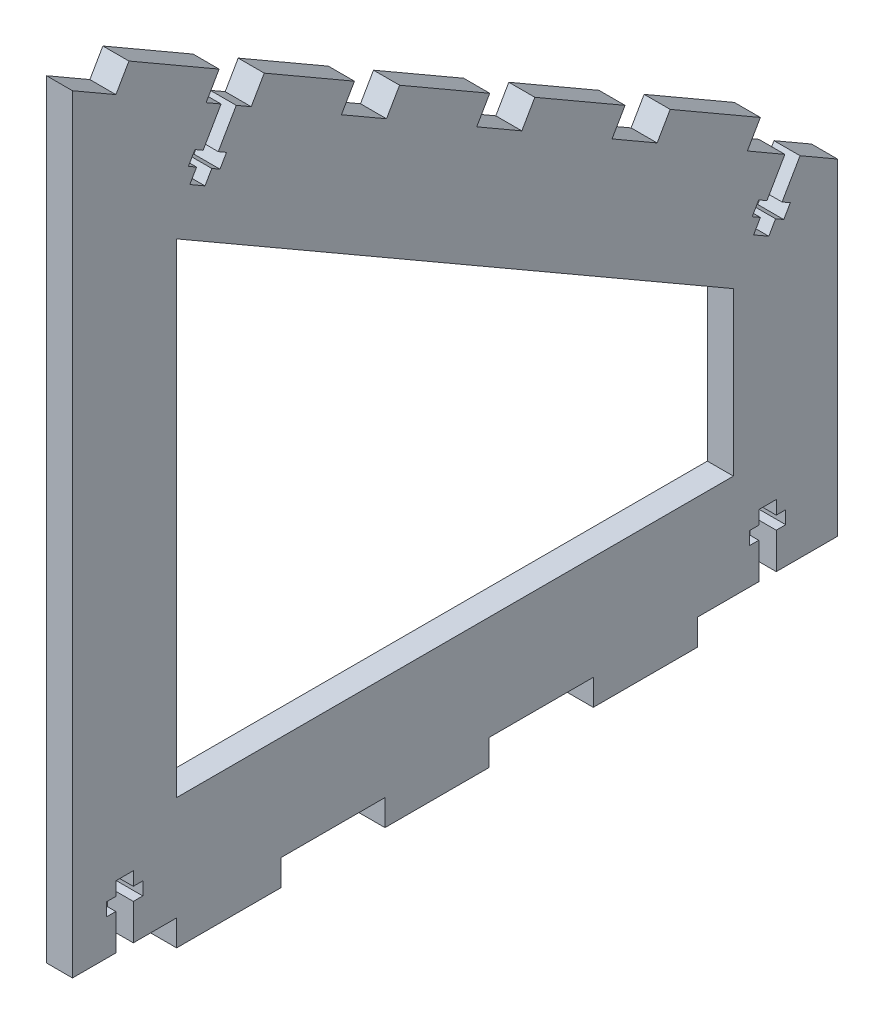
SolidWorks part; units mm, degrees
ref_plane "Front Plane" through (0, 0, 0) normal (0, 0, 1) x (1, 0, 0)
ref_plane "Top Plane" through (0, 0, 0) normal (0, 1, 0) x (1, 0, 0)
ref_plane "Right Plane" through (0, 0, 0) normal (1, 0, 0) x (0, 0, -1)
sketch "Sketch1" plane through (-32.0384, 0, 0) normal (-1, 0, 0) x (0, 0, 1)
  line L0 (-215.9, 95.25) -> (-215.9, 174.9125)
  line L1 (165.3114, 95.25) -> (152.9655, 95.25) construction
  line L2 (-215.9, 174.9125) -> (-29.3333, 282.6268)
  line L3 (-29.3333, 282.6268) -> (-29.3333, 95.25)
  line L4 (-29.3333, 95.25) -> (-215.9, 95.25)
  line L5 (-29.3333, 282.6268) -> (-40.1822, 276.3632) construction
  line L6 (-29.3333, 95.25) -> (-29.3333, 282.6268) construction
extrude "Boss-Extrude1" add sketch "Sketch1" along normal mid plane 6.35
sketch "Sketch2" plane through (-35.2134, 0, 0) normal (-1, 0, 0) x (0, 0, 1)
  line L4 (-190.5, 160.2478) -> (-190.5, 120.65)
  line L5 (-190.5, 160.2478) -> (-190.5, 120.65)
  line L14 (-54.7333, 120.65) -> (-54.7333, 238.6327)
  line L15 (-190.5, 120.65) -> (-54.7333, 120.65)
  line L16 (-54.7333, 238.6327) -> (-190.5, 160.2478)
  line L17 (-54.7333, 120.65) -> (-54.7333, 238.6327)
  line L18 (-190.5, 120.65) -> (-54.7333, 120.65)
  line L19 (-54.7333, 238.6327) -> (-190.5, 160.2478)
  dimension "D1" = 25.4
extrude "Cut-Extrude1" cut sketch "Sketch2" against normal blind 6.35
sketch "Sketch3" plane through (0, 224.6718, -129.7143) normal (0, 0.866, -0.5) x (1, 0, 0)
  line L0 (-35.2134, -115.91) -> (-35.2134, 99.5186) construction
  line L1 (-35.2134, 74.1186) -> (-28.8634, 74.1186)
  line L2 (-35.2134, 74.1186) -> (-35.2134, 48.7186)
  line L3 (-35.2134, 48.7186) -> (-28.8634, 48.7186)
  line L4 (-28.8634, 74.1186) -> (-28.8634, 48.7186)
  line L5 (-28.8634, -115.91) -> (-28.8634, 99.5186) construction
  dimension "D1" = 25.4
  dimension "D2" = 25.4
extrude "Boss-Extrude2" add sketch "Sketch3" along normal blind 6.35
pattern_linear "LPattern1" count 5 spacing 38.1 along (0, 0.5, 0.866) of "Boss-Extrude2"
sketch "Sketch4" plane through (0, 95.25, 0) normal (0, -1, 0) x (1, 0, 0)
  line L0 (-35.2134, -215.9) -> (-35.2134, -29.3333) construction
  line L1 (-35.2134, -54.7333) -> (-28.8634, -54.7333)
  line L2 (-35.2134, -54.7333) -> (-35.2134, -80.1333)
  line L3 (-35.2134, -80.1333) -> (-28.8634, -80.1333)
  line L4 (-28.8634, -54.7333) -> (-28.8634, -80.1333)
  line L5 (-28.8634, -215.9) -> (-28.8634, -29.3333) construction
  dimension "D1" = 25.4
  dimension "D2" = 25.4
extrude "Boss-Extrude3" add sketch "Sketch4" along normal blind 6.35
pattern_linear "LPattern2" count 3 spacing 50.8 along (0, 0, -1) of "Boss-Extrude3"
sketch "Sketch5" plane through (-28.8634, 0, 0) normal (1, 0, 0) x (0, 0, -1)
  line L0 (-152.9655, 95.25) -> (-165.3114, 95.25) construction
  line L1 (198.8167, 95.25) -> (198.8167, 119.6237) construction
  line L2 (215.9, 95.25) -> (181.7333, 95.25) construction
  line L3 (42.0333, 95.25) -> (42.0333, 127.2639) construction
  line L4 (54.7333, 95.25) -> (29.3333, 95.25) construction
  line L5 (-152.9655, 95.25) -> (-165.3114, 95.25) construction
  line B0 (196.6831, 95.25) -> (200.9503, 95.25)
  line B1 (200.9503, 107.188) -> (203.2617, 107.188)
  line B2 (203.2617, 107.188) -> (203.2617, 104.013)
  line B3 (203.2617, 104.013) -> (200.9503, 104.013)
  line B4 (200.9503, 104.013) -> (200.9503, 95.25)
  line B5 (200.9503, 107.188) -> (200.9503, 110.49)
  line B6 (200.9503, 110.49) -> (196.6831, 110.49)
  line B7 (196.6831, 107.188) -> (196.6831, 110.49)
  line B8 (196.6831, 104.013) -> (196.6831, 95.25)
  line B9 (194.3717, 104.013) -> (196.6831, 104.013)
  line B10 (194.3717, 107.188) -> (194.3717, 104.013)
  line B11 (196.6831, 107.188) -> (194.3717, 107.188)
  line B12 (39.8997, 95.25) -> (44.1669, 95.25)
  line B13 (44.1669, 107.188) -> (46.4783, 107.188)
  line B14 (46.4783, 107.188) -> (46.4783, 104.013)
  line B15 (46.4783, 104.013) -> (44.1669, 104.013)
  line B16 (44.1669, 104.013) -> (44.1669, 95.25)
  line B17 (44.1669, 107.188) -> (44.1669, 110.49)
  line B18 (44.1669, 110.49) -> (39.8997, 110.49)
  line B19 (39.8997, 107.188) -> (39.8997, 110.49)
  line B20 (39.8997, 104.013) -> (39.8997, 95.25)
  line B21 (37.5883, 104.013) -> (39.8997, 104.013)
  line B22 (37.5883, 107.188) -> (37.5883, 104.013)
  line B23 (39.8997, 107.188) -> (37.5883, 107.188)
sketch_block_instance "TSlot-1"
sketch_block "TSlot" parameters "D1"=3.302, "D2"=3.175
sketch_block_instance "TSlot-3"
extrude "Cut-Extrude2" cut sketch "Sketch5" against normal blind 6.35
sketch "Sketch6" plane through (-28.8634, 0, 0) normal (1, 0, 0) x (0, 0, -1)
  line L1 (51.3304, 269.9268) -> (73.3274, 257.2268) construction
  line L3 (183.3127, 193.7268) -> (205.3097, 181.0268) construction
  line L4 (204.9015, 181.2625) -> (174.0343, 127.799) construction
  line L5 (193.903, 187.6125) -> (215.9, 174.9125) construction
  line L6 (67.4199, 260.6375) -> (38.3031, 210.2056) construction
  line L7 (61.9207, 263.8125) -> (72.9192, 257.4625) construction
  line B0 (206.7492, 180.1957) -> (203.0537, 182.3293)
  line B1 (197.0847, 171.9907) -> (195.083, 173.1464)
  line B2 (195.083, 173.1464) -> (196.6705, 175.896)
  line B3 (196.6705, 175.896) -> (198.6722, 174.7403)
  line B4 (198.6722, 174.7403) -> (203.0537, 182.3293)
  line B5 (197.0847, 171.9907) -> (195.4337, 169.1311)
  line B6 (195.4337, 169.1311) -> (199.1292, 166.9975)
  line B7 (200.7802, 169.8571) -> (199.1292, 166.9975)
  line B8 (202.3677, 172.6067) -> (206.7492, 180.1957)
  line B9 (204.3695, 171.451) -> (202.3677, 172.6067)
  line B10 (202.782, 168.7014) -> (204.3695, 171.451)
  line B11 (200.7802, 169.8571) -> (202.782, 168.7014)
  line B12 (69.2677, 259.5707) -> (65.5722, 261.7043)
  line B13 (59.6032, 251.3657) -> (57.6015, 252.5214)
  line B14 (57.6015, 252.5214) -> (59.189, 255.271)
  line B15 (59.189, 255.271) -> (61.1907, 254.1153)
  line B16 (61.1907, 254.1153) -> (65.5722, 261.7043)
  line B17 (59.6032, 251.3657) -> (57.9522, 248.5061)
  line B18 (57.9522, 248.5061) -> (61.6477, 246.3725)
  line B19 (63.2987, 249.2321) -> (61.6477, 246.3725)
  line B20 (64.8862, 251.9817) -> (69.2677, 259.5707)
  line B21 (66.8879, 250.826) -> (64.8862, 251.9817)
  line B22 (65.3004, 248.0764) -> (66.8879, 250.826)
  line B23 (63.2987, 249.2321) -> (65.3004, 248.0764)
sketch_block_instance "TSlot-4"
sketch_block_instance "TSlot-5"
extrude "Cut-Extrude3" cut sketch "Sketch6" against normal blind 6.35
